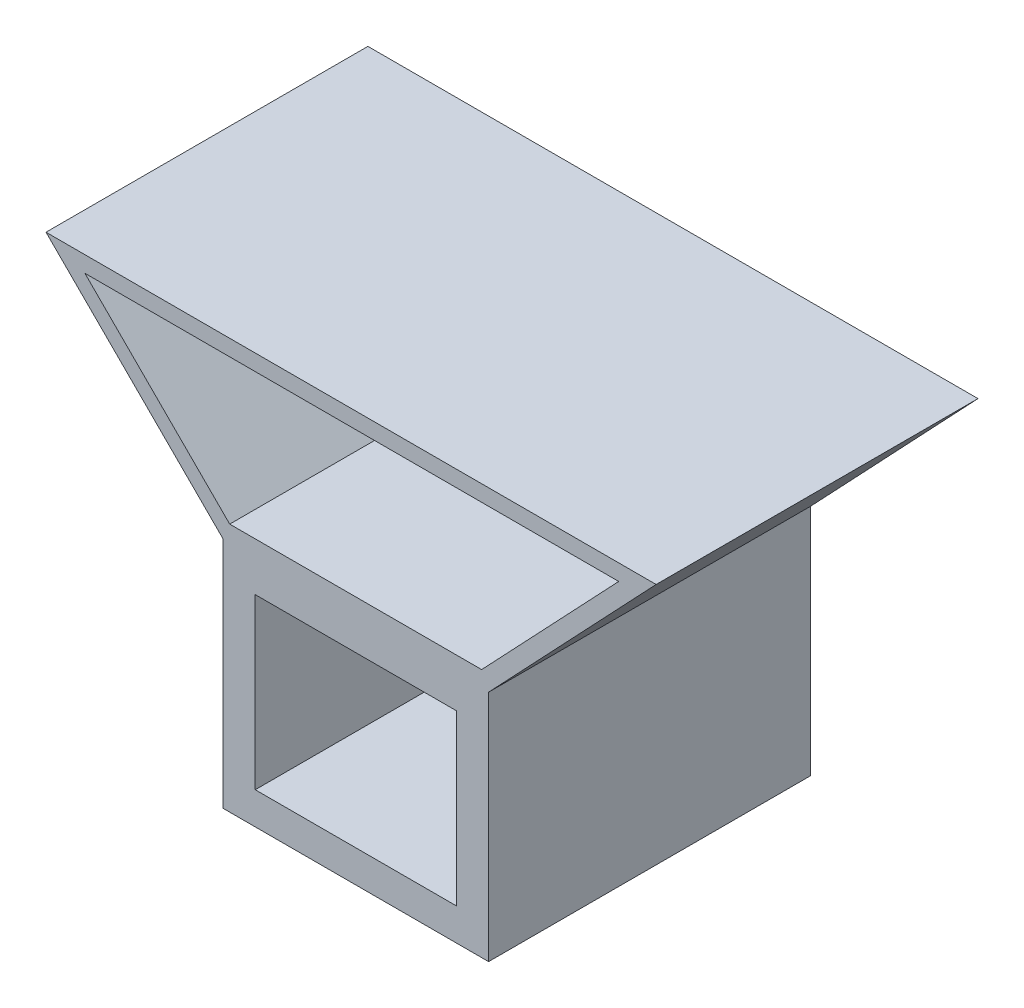
SolidWorks part; units mm, degrees
ref_plane "Front Plane" through (0, 0, 0) normal (0, 0, 1) x (1, 0, 0)
ref_plane "Top Plane" through (0, 0, 0) normal (0, 1, 0) x (1, 0, 0)
ref_plane "Right Plane" through (0, 0, 0) normal (1, 0, 0) x (0, 0, -1)
sketch "Sketch1" plane through (0, 0, 0) normal (0, 0, 1) x (1, 0, 0)
  line L0 (-2, -2) -> (-2, 12.5)
  line L1 (0, 0) -> (12.5, 0)
  line L2 (0, 0) -> (0, 10.5)
  line L3 (0, 10.5) -> (12.5, 10.5)
  line L4 (12.5, 0) -> (12.5, 10.5)
  line L5 (-2, 12.5) -> (14.5, 12.5)
  line L6 (14.5, -2) -> (14.5, 12.5)
  line L7 (-2, -2) -> (14.5, -2)
  line L8 (-7.2977, 5) -> (18.7002, 5) construction
  dimension "D1" = 12.5
  dimension "D2" = 10.5
  dimension "D4" = 2
  dimension "D3" = 2
  dimension "D5" = 2
  dimension "D6" = 2
extrude "Boss-Extrude1" add sketch "Sketch1" along normal blind 20
sketch "Sketch2" plane through (0, 0, 0) normal (0, 0, -1) x (-1, 0, 0)
  line L0 (2, 12.5) -> (2, 23.5) construction
  line L1 (2, 12.5) -> (13, 23.5)
  line L2 (-14.5, 12.5) -> (-14.5, 23.5) construction
  line L3 (-24.9079, 23.5) -> (-14.5, 12.5)
  line L4 (-24.9079, 23.5) -> (13, 23.5)
  line L5 (-14.5, 12.5) -> (2, 12.5)
  line L10 (-22.5851, 22.5) -> (-14.0695, 13.5)
  line L11 (-14.0695, 13.5) -> (1.5858, 13.5)
  line L12 (1.5858, 13.5) -> (10.5858, 22.5)
  line L13 (-22.5851, 22.5) -> (10.5858, 22.5)
  dimension "D1" = 11
  dimension "D2" = 45
  dimension "D3" = 1
  dimension "D4" = 11
extrude "Boss-Extrude2" add sketch "Sketch2" against normal blind 20 contours L10 L11 L12 L13
